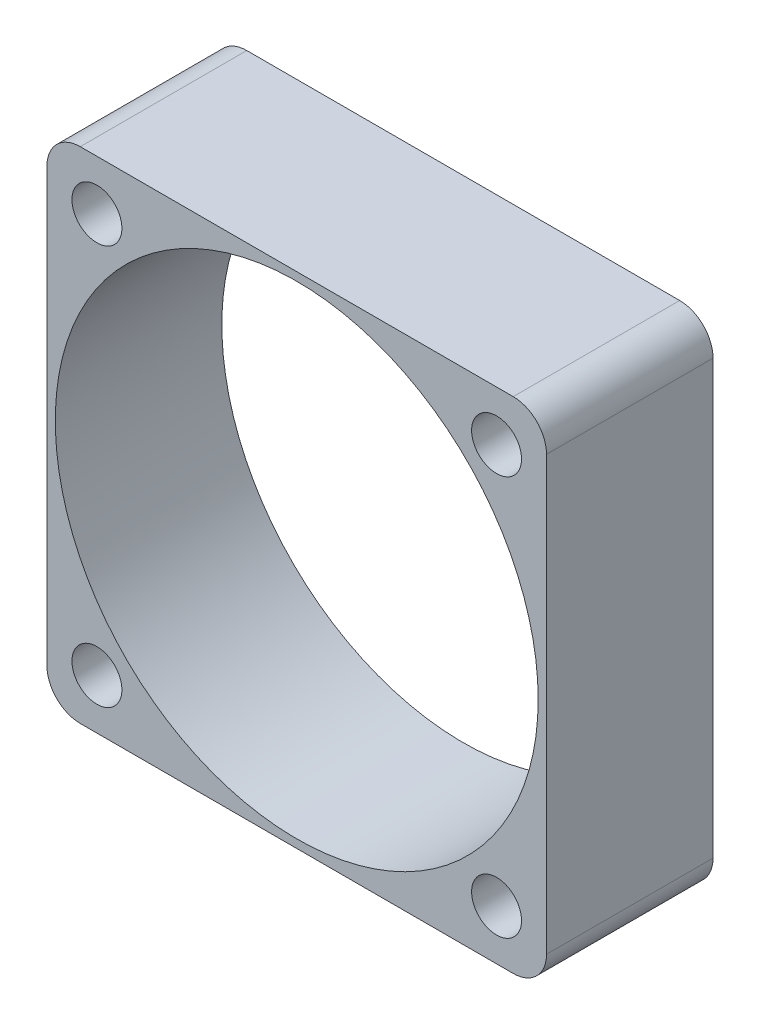
SolidWorks part; units mm, degrees
ref_plane "前基準面" through (0, 0, 0) normal (0, 0, 1) x (1, 0, 0)
ref_plane "上基準面" through (0, 0, 0) normal (0, 1, 0) x (1, 0, 0)
ref_plane "右基準面" through (0, 0, 0) normal (1, 0, 0) x (0, 0, -1)
sketch "草圖1" plane through (0, 0, 0) normal (0, 0, 1) x (1, 0, 0)
  line L1 (-15, 15) -> (15, 15)
  line L2 (-15, 15) -> (-15, -15)
  line L3 (-15, -15) -> (15, -15)
  line L4 (15, 15) -> (15, -15)
  circle A0 centre (0, 0) radius 14.5
  point P4 (0, 15)
  point P6 (-15, 0)
  dimension "D3" = 29
  dimension "D1" = 30
  dimension "D2" = 30
extrude "填料-伸長1" add sketch "草圖1" along normal blind 10
fillet "圓角1" radius 2 4 edges at (-15, -15, 5) (15, -15, 5) (15, 15, 5) (-15, 15, 5)
sketch "草圖2" plane through (0, 0, 10) normal (0, 0, 1) x (1, 0, 0)
  line L0 (-15, 0) -> (15, 0) construction
  line L1 (-15, 13) -> (-15, -13) construction
  line L2 (15, -13) -> (15, 13) construction
  line L3 (0, 15) -> (0, -15) construction
  line L4 (13, 15) -> (-13, 15) construction
  line L5 (-13, -15) -> (13, -15) construction
  circle A0 centre (-12, 12) radius 1.5
  circle A1 centre (12, 12) radius 1.5
  circle A2 centre (12, -12) radius 1.5
  circle A3 centre (-12, -12) radius 1.5
  dimension "D1" = 3
  dimension "D2" = 12
  dimension "D3" = 12
extrude "除料-伸長1" cut sketch "草圖2" against normal blind 10
